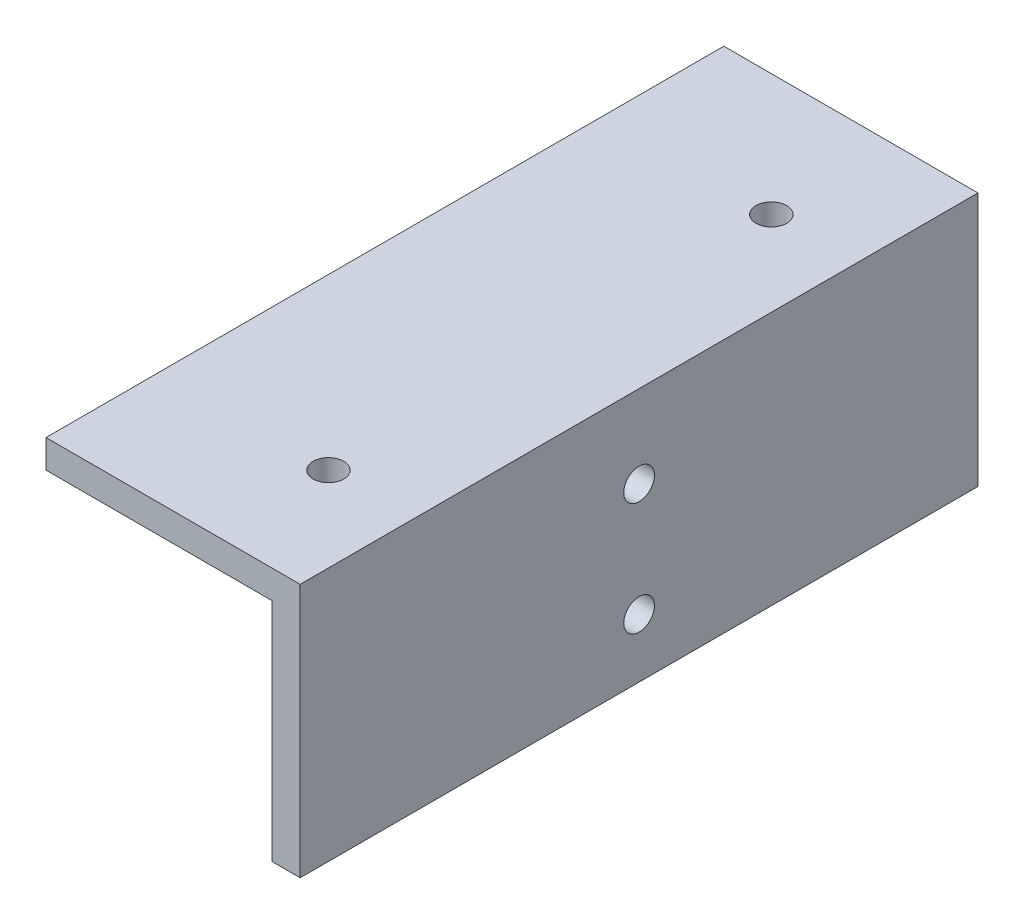
SolidWorks part; units mm, degrees
ref_plane "Front Plane" through (0, 0, 0) normal (0, 0, 1) x (1, 0, 0)
ref_plane "Top Plane" through (0, 0, 0) normal (0, 1, 0) x (1, 0, 0)
ref_plane "Right Plane" through (0, 0, 0) normal (1, 0, 0) x (0, 0, -1)
sketch "Sketch1" plane through (0, 0, 0) normal (0, 0, 1) x (1, 0, 0)
  line L0 (0, 0) -> (0, 28.575)
  line L1 (0, 28.575) -> (-28.575, 28.575)
  line L2 (-28.575, 28.575) -> (-28.575, 25.4)
  line L3 (-28.575, 25.4) -> (-3.175, 25.4)
  line L4 (-3.175, 25.4) -> (-3.175, 0)
  line L5 (-3.175, 0) -> (0, 0)
  dimension "D1" = 25.4
  dimension "D2" = 3.175
  dimension "D3" = 3.175
  dimension "D4" = 28.575
extrude "Boss-Extrude1" add sketch "Sketch1" along normal blind 76.2
hole_wizard "Tap Drill for #8-36 Tap1" positions "Sketch3" profile "Sketch2" hole size "#8-36" standard "ANSI Inch" end condition up to next
sketch "Sketch3" plane through (-3.175, 0, 0) normal (-1, 0, 0) x (0, 0, 1)
  point P0 (38.1, 6.6)
  point P3 (38.1, 19.3)
sketch "Sketch2" plane through (-3.175, 6.6, 38.1) normal (0, 1, 0) x (0, 0, 1)
  line L0 (0, 0) -> (0, 3.175)
  line L1 (0, 3.175) -> (1.7272, 3.175)
  line L2 (1.7272, 3.175) -> (1.7272, 0)
  line L5 (1.7272, 0) -> (0, 0)
  line L11 (0, -6.35) -> (0, 107.95) construction
  dimension "Thru Hole Dia." = 3.4544
  dimension "Thru Hole Depth" = 3.175
hole_wizard "Tap Drill for #8-36 Tap2" positions "Sketch5" profile "Sketch4" hole size "#8-36" standard "ANSI Inch" end condition up to next
sketch "Sketch5" plane through (0, 25.4, 0) normal (0, -1, 0) x (-1, 0, 0)
  line L0 (28.575, -76.2) -> (3.175, -76.2) construction
  line L1 (28.575, -76.2) -> (28.575, 0) construction
  point P0 (9.525, -63.5)
  point P2 (-28.575, -63.5)
  point P4 (9.525, -13.7116)
  point P6 (-28.575, -13.7116)
  dimension "D1" = 38.1
  dimension "D2" = 12.7
  dimension "D3" = 19.05
sketch "Sketch4" plane through (-9.525, 25.4, 63.5) normal (1, 0, 0) x (0, 0, -1)
  line L0 (0, 0) -> (0, 3.175)
  line L1 (0, 3.175) -> (1.7272, 3.175)
  line L2 (1.7272, 3.175) -> (1.7272, 0)
  line L5 (1.7272, 0) -> (0, 0)
  line L11 (0, -6.35) -> (0, 107.95) construction
  dimension "Thru Hole Dia." = 3.4544
  dimension "Thru Hole Depth" = 3.175
